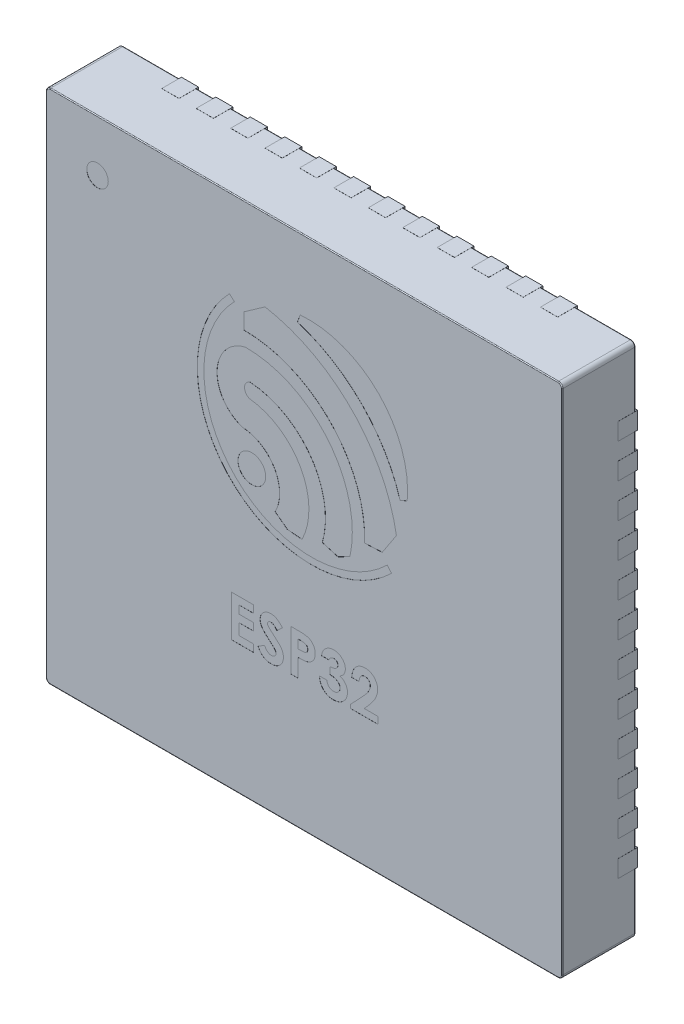
SolidWorks part; units mm, degrees
other "ESP32-SoC-6x6" parameters "D5"=0.3678, "D1"=3.1308, "D2"=3.0402, "D3"=0.4115, "D4"=0.3, "D6"=0.3296, "D7"=0.2637, "D8"=0.9806, "D10"=0.4, "D11"=0.25, "D9"=6
ref_plane "Front Plane" through (0, 0, 0) normal (0, 0, 1) x (1, 0, 0)
ref_plane "Top Plane" through (0, 0, 0) normal (0, 1, 0) x (1, 0, 0)
ref_plane "Right Plane" through (0, 0, 0) normal (1, 0, 0) x (0, 0, -1)
sketch "Sketch1" plane through (0, 0, 0) normal (0, 1, 0) x (1, 0, 0)
  line L1 (-3, -3) -> (3, -3)
  line L2 (-3, -3) -> (-3, 3)
  line L3 (-3, 3) -> (3, 3)
  line L4 (3, -3) -> (3, 3)
  line L5 (-3, -3) -> (3, 3) construction
  line L6 (-3, 3) -> (3, -3) construction
  point P0 (0, 0)
  dimension "D1" = 6
  dimension "D2" = 6
extrude "Boss-Extrude1" add sketch "Sketch1" along normal blind 0.85
fillet "Fillet1" radius 0.05 4 edges at (3, 0.425, -3) (3, 0.425, 3) (-3, 0.425, 3) (-3, 0.425, -3)
fillet "Fillet2" radius 0.01 16 edges at (2.9854, 0.85, 2.9854) (0, 0.85, 3) (-2.9854, 0.85, 2.9854) (-3, 0.85, 0) (-2.9854, 0.85, -2.9854) (0, 0.85, -3) (2.9854, 0.85, -2.9854) (3, 0.85, 0) (3, 0, 0) (2.9854, 0, -2.9854) (0, 0, -3) (2.9854, 0, 2.9854) (0, 0, 3) (-2.9854, 0, 2.9854) (-3, 0, 0) (-2.9854, 0, -2.9854)
sketch "Sketch2" plane through (0, 0, 0) normal (0, -1, 0) x (1, 0, 0)
  line L0 (1.85, 2.15) -> (2.15, 1.85)
  line L1 (-2.05, -2.15) -> (2.05, -2.15)
  line L2 (-2.15, -2.05) -> (-2.15, 2.05)
  line L3 (-2.05, 2.15) -> (1.85, 2.15)
  line L4 (2.15, -2.05) -> (2.15, 1.85)
  line L5 (-2.1207, -2.1207) -> (2.15, 2.15) construction
  line L6 (-2.1207, 2.1207) -> (2.1207, -2.1207) construction
  line L7 (1.85, 2.15) -> (2.15, 2.15) construction
  line L8 (2.15, 1.85) -> (2.15, 2.15) construction
  line L9 (-2.15, 2.15) -> (-2.05, 2.15) construction
  line L10 (-2.15, 2.15) -> (-2.1207, 2.1207) construction
  line L11 (-2.15, 2.05) -> (-2.15, 2.15) construction
  line L12 (-2.15, -2.15) -> (-2.15, -2.05) construction
  line L13 (-2.15, -2.15) -> (-2.1207, -2.1207) construction
  line L14 (-2.15, -2.15) -> (-2.05, -2.15) construction
  line L15 (2.15, -2.15) -> (2.15, -2.05) construction
  line L16 (2.1207, -2.1207) -> (2.15, -2.15) construction
  line L17 (2.05, -2.15) -> (2.15, -2.15) construction
  line L18 (0, -1000) -> (0, 49000) construction
  line L23 (-0.3, 3.001) -> (-0.1, 3.001)
  line L24 (-0.3, 3.001) -> (-0.3, 2.601)
  line L25 (-0.3, 2.601) -> (-0.1, 2.601)
  line L26 (-0.1, 3.001) -> (-0.1, 2.601)
  line L27 (-0.3, 3.001) -> (-0.1, 2.601) construction
  line L28 (-0.3, 2.601) -> (-0.1, 3.001) construction
  line L30 (-0.7, 3.001) -> (-0.7, 2.601)
  line L31 (-0.7, 3.001) -> (-0.5, 3.001)
  line L32 (-0.5, 3.001) -> (-0.5, 2.601)
  line L33 (-0.7, 2.601) -> (-0.5, 2.601)
  line L34 (-0.7, 2.601) -> (-0.5, 3.001) construction
  line L35 (-0.7, 3.001) -> (-0.5, 2.601) construction
  line L36 (-1.1, 3.001) -> (-1.1, 2.601)
  line L37 (-1.1, 3.001) -> (-0.9, 3.001)
  line L38 (-0.9, 3.001) -> (-0.9, 2.601)
  line L39 (-1.1, 2.601) -> (-0.9, 2.601)
  line L40 (-1.1, 2.601) -> (-0.9, 3.001) construction
  line L41 (-1.1, 3.001) -> (-0.9, 2.601) construction
  line L42 (-1.5, 3.001) -> (-1.5, 2.601)
  line L43 (-1.5, 3.001) -> (-1.3, 3.001)
  line L44 (-1.3, 3.001) -> (-1.3, 2.601)
  line L45 (-1.5, 2.601) -> (-1.3, 2.601)
  line L46 (-1.5, 2.601) -> (-1.3, 3.001) construction
  line L47 (-1.5, 3.001) -> (-1.3, 2.601) construction
  line L48 (-0.3, 3.001) -> (-0.7, 3.001) construction
  line L49 (-1.9, 3.001) -> (-1.9, 2.601)
  line L66 (-1.9, 3.001) -> (-1.7, 3.001)
  line L162 (-1000, 0) -> (49000, 0) construction
  line L163 (-3, 3) -> (3, 3) construction
  line L164 (-1.7, 3.001) -> (-1.7, 2.601)
  line L165 (-1.9, 2.601) -> (-1.7, 2.601)
  line L166 (-1.9, 2.601) -> (-1.7, 3.001) construction
  line L167 (-1.9, 3.001) -> (-1.7, 2.601) construction
  line L168 (-2.3, 3.001) -> (-2.3, 2.601)
  line L169 (-2.3, 3.001) -> (-2.1, 3.001)
  line L170 (-2.1, 3.001) -> (-2.1, 2.601)
  line L171 (-2.3, 2.601) -> (-2.1, 2.601)
  line L172 (-2.3, 2.601) -> (-2.1, 3.001) construction
  line L173 (-2.3, 3.001) -> (-2.1, 2.601) construction
  line L174 (2.3, 3.001) -> (2.1, 2.601) construction
  line L175 (2.3, 2.601) -> (2.1, 3.001) construction
  line L176 (1.9, 3.001) -> (1.7, 2.601) construction
  line L177 (1.9, 2.601) -> (1.7, 3.001) construction
  line L178 (0.3, 3.001) -> (0.7, 3.001) construction
  line L179 (1.5, 3.001) -> (1.3, 2.601) construction
  line L180 (1.5, 2.601) -> (1.3, 3.001) construction
  line L181 (1.1, 3.001) -> (0.9, 2.601) construction
  line L182 (1.1, 2.601) -> (0.9, 3.001) construction
  line L183 (0.7, 3.001) -> (0.5, 2.601) construction
  line L184 (0.7, 2.601) -> (0.5, 3.001) construction
  line L185 (0.3, 2.601) -> (0.1, 3.001) construction
  line L186 (0.3, 3.001) -> (0.1, 2.601) construction
  line L187 (2.3, 2.601) -> (2.1, 2.601)
  line L188 (2.1, 3.001) -> (2.1, 2.601)
  line L189 (2.3, 3.001) -> (2.1, 3.001)
  line L190 (2.3, 3.001) -> (2.3, 2.601)
  line L191 (1.9, 2.601) -> (1.7, 2.601)
  line L192 (1.7, 3.001) -> (1.7, 2.601)
  line L193 (1.9, 3.001) -> (1.7, 3.001)
  line L194 (1.9, 3.001) -> (1.9, 2.601)
  line L195 (1.5, 2.601) -> (1.3, 2.601)
  line L196 (1.3, 3.001) -> (1.3, 2.601)
  line L197 (1.5, 3.001) -> (1.3, 3.001)
  line L198 (1.5, 3.001) -> (1.5, 2.601)
  line L199 (1.1, 2.601) -> (0.9, 2.601)
  line L200 (0.9, 3.001) -> (0.9, 2.601)
  line L201 (1.1, 3.001) -> (0.9, 3.001)
  line L202 (1.1, 3.001) -> (1.1, 2.601)
  line L203 (0.7, 2.601) -> (0.5, 2.601)
  line L204 (0.5, 3.001) -> (0.5, 2.601)
  line L205 (0.7, 3.001) -> (0.5, 3.001)
  line L206 (0.7, 3.001) -> (0.7, 2.601)
  line L207 (0.1, 3.001) -> (0.1, 2.601)
  line L208 (0.3, 2.601) -> (0.1, 2.601)
  line L209 (0.3, 3.001) -> (0.3, 2.601)
  line L210 (0.3, 3.001) -> (0.1, 3.001)
  line L211 (0.3, -3.001) -> (0.1, -2.601) construction
  line L212 (0.3, -2.601) -> (0.1, -3.001) construction
  line L213 (0.7, -2.601) -> (0.5, -3.001) construction
  line L214 (0.7, -3.001) -> (0.5, -2.601) construction
  line L215 (1.1, -2.601) -> (0.9, -3.001) construction
  line L216 (1.1, -3.001) -> (0.9, -2.601) construction
  line L217 (1.5, -2.601) -> (1.3, -3.001) construction
  line L218 (1.5, -3.001) -> (1.3, -2.601) construction
  line L219 (0.3, -3.001) -> (0.7, -3.001) construction
  line L220 (1.9, -2.601) -> (1.7, -3.001) construction
  line L221 (1.9, -3.001) -> (1.7, -2.601) construction
  line L222 (2.3, -2.601) -> (2.1, -3.001) construction
  line L223 (2.3, -3.001) -> (2.1, -2.601) construction
  line L224 (-2.3, -3.001) -> (-2.1, -2.601) construction
  line L225 (-2.3, -2.601) -> (-2.1, -3.001) construction
  line L226 (-1.9, -3.001) -> (-1.7, -2.601) construction
  line L227 (-1.9, -2.601) -> (-1.7, -3.001) construction
  line L228 (-0.3, -3.001) -> (-0.7, -3.001) construction
  line L229 (-1.5, -3.001) -> (-1.3, -2.601) construction
  line L230 (-1.5, -2.601) -> (-1.3, -3.001) construction
  line L231 (-1.1, -3.001) -> (-0.9, -2.601) construction
  line L232 (-1.1, -2.601) -> (-0.9, -3.001) construction
  line L233 (-0.7, -3.001) -> (-0.5, -2.601) construction
  line L234 (-0.7, -2.601) -> (-0.5, -3.001) construction
  line L235 (-0.3, -2.601) -> (-0.1, -3.001) construction
  line L236 (-0.3, -3.001) -> (-0.1, -2.601) construction
  line L237 (0.3, -3.001) -> (0.1, -3.001)
  line L238 (0.3, -3.001) -> (0.3, -2.601)
  line L239 (0.3, -2.601) -> (0.1, -2.601)
  line L240 (0.1, -3.001) -> (0.1, -2.601)
  line L241 (0.7, -3.001) -> (0.7, -2.601)
  line L242 (0.7, -3.001) -> (0.5, -3.001)
  line L243 (0.5, -3.001) -> (0.5, -2.601)
  line L244 (0.7, -2.601) -> (0.5, -2.601)
  line L245 (1.1, -3.001) -> (1.1, -2.601)
  line L246 (1.1, -3.001) -> (0.9, -3.001)
  line L247 (0.9, -3.001) -> (0.9, -2.601)
  line L248 (1.1, -2.601) -> (0.9, -2.601)
  line L249 (1.5, -3.001) -> (1.5, -2.601)
  line L250 (1.5, -3.001) -> (1.3, -3.001)
  line L251 (1.3, -3.001) -> (1.3, -2.601)
  line L252 (1.5, -2.601) -> (1.3, -2.601)
  line L253 (1.9, -3.001) -> (1.9, -2.601)
  line L254 (1.9, -3.001) -> (1.7, -3.001)
  line L255 (1.7, -3.001) -> (1.7, -2.601)
  line L256 (1.9, -2.601) -> (1.7, -2.601)
  line L257 (2.3, -3.001) -> (2.3, -2.601)
  line L258 (2.3, -3.001) -> (2.1, -3.001)
  line L259 (2.1, -3.001) -> (2.1, -2.601)
  line L260 (2.3, -2.601) -> (2.1, -2.601)
  line L261 (-2.3, -2.601) -> (-2.1, -2.601)
  line L262 (-2.1, -3.001) -> (-2.1, -2.601)
  line L263 (-2.3, -3.001) -> (-2.1, -3.001)
  line L264 (-2.3, -3.001) -> (-2.3, -2.601)
  line L265 (-1.9, -2.601) -> (-1.7, -2.601)
  line L266 (-1.7, -3.001) -> (-1.7, -2.601)
  line L267 (-1.9, -3.001) -> (-1.7, -3.001)
  line L268 (-1.9, -3.001) -> (-1.9, -2.601)
  line L269 (-1.5, -2.601) -> (-1.3, -2.601)
  line L270 (-1.3, -3.001) -> (-1.3, -2.601)
  line L271 (-1.5, -3.001) -> (-1.3, -3.001)
  line L272 (-1.5, -3.001) -> (-1.5, -2.601)
  line L273 (-1.1, -2.601) -> (-0.9, -2.601)
  line L274 (-0.9, -3.001) -> (-0.9, -2.601)
  line L275 (-1.1, -3.001) -> (-0.9, -3.001)
  line L276 (-1.1, -3.001) -> (-1.1, -2.601)
  line L277 (-0.7, -2.601) -> (-0.5, -2.601)
  line L278 (-0.5, -3.001) -> (-0.5, -2.601)
  line L279 (-0.7, -3.001) -> (-0.5, -3.001)
  line L280 (-0.7, -3.001) -> (-0.7, -2.601)
  line L281 (-0.1, -3.001) -> (-0.1, -2.601)
  line L282 (-0.3, -2.601) -> (-0.1, -2.601)
  line L283 (-0.3, -3.001) -> (-0.3, -2.601)
  line L284 (-0.3, -3.001) -> (-0.1, -3.001)
  line L285 (3.001, 0.3) -> (2.601, 0.1) construction
  line L286 (2.601, 0.3) -> (3.001, 0.1) construction
  line L287 (2.601, 0.7) -> (3.001, 0.5) construction
  line L288 (3.001, 0.7) -> (2.601, 0.5) construction
  line L289 (2.601, 1.1) -> (3.001, 0.9) construction
  line L290 (3.001, 1.1) -> (2.601, 0.9) construction
  line L291 (2.601, 1.5) -> (3.001, 1.3) construction
  line L292 (3.001, 1.5) -> (2.601, 1.3) construction
  line L293 (3.001, 0.3) -> (3.001, 0.7) construction
  line L294 (2.601, 1.9) -> (3.001, 1.7) construction
  line L295 (3.001, 1.9) -> (2.601, 1.7) construction
  line L296 (2.601, 2.3) -> (3.001, 2.1) construction
  line L297 (3.001, 2.3) -> (2.601, 2.1) construction
  line L298 (3.001, -2.3) -> (2.601, -2.1) construction
  line L299 (2.601, -2.3) -> (3.001, -2.1) construction
  line L300 (3.001, -1.9) -> (2.601, -1.7) construction
  line L301 (2.601, -1.9) -> (3.001, -1.7) construction
  line L302 (3.001, -0.3) -> (3.001, -0.7) construction
  line L303 (3.001, -1.5) -> (2.601, -1.3) construction
  line L304 (2.601, -1.5) -> (3.001, -1.3) construction
  line L305 (3.001, -1.1) -> (2.601, -0.9) construction
  line L306 (2.601, -1.1) -> (3.001, -0.9) construction
  line L307 (3.001, -0.7) -> (2.601, -0.5) construction
  line L308 (2.601, -0.7) -> (3.001, -0.5) construction
  line L309 (2.601, -0.3) -> (3.001, -0.1) construction
  line L310 (3.001, -0.3) -> (2.601, -0.1) construction
  line L311 (3.001, 0.3) -> (3.001, 0.1)
  line L312 (3.001, 0.3) -> (2.601, 0.3)
  line L313 (2.601, 0.3) -> (2.601, 0.1)
  line L314 (3.001, 0.1) -> (2.601, 0.1)
  line L315 (3.001, 0.7) -> (2.601, 0.7)
  line L316 (3.001, 0.7) -> (3.001, 0.5)
  line L317 (3.001, 0.5) -> (2.601, 0.5)
  line L318 (2.601, 0.7) -> (2.601, 0.5)
  line L319 (3.001, 1.1) -> (2.601, 1.1)
  line L320 (3.001, 1.1) -> (3.001, 0.9)
  line L321 (3.001, 0.9) -> (2.601, 0.9)
  line L322 (2.601, 1.1) -> (2.601, 0.9)
  line L323 (3.001, 1.5) -> (2.601, 1.5)
  line L324 (3.001, 1.5) -> (3.001, 1.3)
  line L325 (3.001, 1.3) -> (2.601, 1.3)
  line L326 (2.601, 1.5) -> (2.601, 1.3)
  line L327 (3.001, 1.9) -> (2.601, 1.9)
  line L328 (3.001, 1.9) -> (3.001, 1.7)
  line L329 (3.001, 1.7) -> (2.601, 1.7)
  line L330 (2.601, 1.9) -> (2.601, 1.7)
  line L331 (3.001, 2.3) -> (2.601, 2.3)
  line L332 (3.001, 2.3) -> (3.001, 2.1)
  line L333 (3.001, 2.1) -> (2.601, 2.1)
  line L334 (2.601, 2.3) -> (2.601, 2.1)
  line L335 (2.601, -2.3) -> (2.601, -2.1)
  line L336 (3.001, -2.1) -> (2.601, -2.1)
  line L337 (3.001, -2.3) -> (3.001, -2.1)
  line L338 (3.001, -2.3) -> (2.601, -2.3)
  line L339 (2.601, -1.9) -> (2.601, -1.7)
  line L340 (3.001, -1.7) -> (2.601, -1.7)
  line L341 (3.001, -1.9) -> (3.001, -1.7)
  line L342 (3.001, -1.9) -> (2.601, -1.9)
  line L343 (2.601, -1.5) -> (2.601, -1.3)
  line L344 (3.001, -1.3) -> (2.601, -1.3)
  line L345 (3.001, -1.5) -> (3.001, -1.3)
  line L346 (3.001, -1.5) -> (2.601, -1.5)
  line L347 (2.601, -1.1) -> (2.601, -0.9)
  line L348 (3.001, -0.9) -> (2.601, -0.9)
  line L349 (3.001, -1.1) -> (3.001, -0.9)
  line L350 (3.001, -1.1) -> (2.601, -1.1)
  line L351 (2.601, -0.7) -> (2.601, -0.5)
  line L352 (3.001, -0.5) -> (2.601, -0.5)
  line L353 (3.001, -0.7) -> (3.001, -0.5)
  line L354 (3.001, -0.7) -> (2.601, -0.7)
  line L355 (3.001, -0.1) -> (2.601, -0.1)
  line L356 (2.601, -0.3) -> (2.601, -0.1)
  line L357 (3.001, -0.3) -> (2.601, -0.3)
  line L358 (3.001, -0.3) -> (3.001, -0.1)
  line L359 (-3.001, -0.3) -> (-2.601, -0.1) construction
  line L360 (-2.601, -0.3) -> (-3.001, -0.1) construction
  line L361 (-2.601, -0.7) -> (-3.001, -0.5) construction
  line L362 (-3.001, -0.7) -> (-2.601, -0.5) construction
  line L363 (-2.601, -1.1) -> (-3.001, -0.9) construction
  line L364 (-3.001, -1.1) -> (-2.601, -0.9) construction
  line L365 (-2.601, -1.5) -> (-3.001, -1.3) construction
  line L366 (-3.001, -1.5) -> (-2.601, -1.3) construction
  line L367 (-3.001, -0.3) -> (-3.001, -0.7) construction
  line L368 (-2.601, -1.9) -> (-3.001, -1.7) construction
  line L369 (-3.001, -1.9) -> (-2.601, -1.7) construction
  line L370 (-2.601, -2.3) -> (-3.001, -2.1) construction
  line L371 (-3.001, -2.3) -> (-2.601, -2.1) construction
  line L372 (-3.001, 2.3) -> (-2.601, 2.1) construction
  line L373 (-2.601, 2.3) -> (-3.001, 2.1) construction
  line L374 (-3.001, 1.9) -> (-2.601, 1.7) construction
  line L375 (-2.601, 1.9) -> (-3.001, 1.7) construction
  line L376 (-3.001, 0.3) -> (-3.001, 0.7) construction
  line L377 (-3.001, 1.5) -> (-2.601, 1.3) construction
  line L378 (-2.601, 1.5) -> (-3.001, 1.3) construction
  line L379 (-3.001, 1.1) -> (-2.601, 0.9) construction
  line L380 (-2.601, 1.1) -> (-3.001, 0.9) construction
  line L381 (-3.001, 0.7) -> (-2.601, 0.5) construction
  line L382 (-2.601, 0.7) -> (-3.001, 0.5) construction
  line L383 (-2.601, 0.3) -> (-3.001, 0.1) construction
  line L384 (-3.001, 0.3) -> (-2.601, 0.1) construction
  line L385 (-3.001, -0.3) -> (-3.001, -0.1)
  line L386 (-3.001, -0.3) -> (-2.601, -0.3)
  line L387 (-2.601, -0.3) -> (-2.601, -0.1)
  line L388 (-3.001, -0.1) -> (-2.601, -0.1)
  line L389 (-3.001, -0.7) -> (-2.601, -0.7)
  line L390 (-3.001, -0.7) -> (-3.001, -0.5)
  line L391 (-3.001, -0.5) -> (-2.601, -0.5)
  line L392 (-2.601, -0.7) -> (-2.601, -0.5)
  line L393 (-3.001, -1.1) -> (-2.601, -1.1)
  line L394 (-3.001, -1.1) -> (-3.001, -0.9)
  line L395 (-3.001, -0.9) -> (-2.601, -0.9)
  line L396 (-2.601, -1.1) -> (-2.601, -0.9)
  line L397 (-3.001, -1.5) -> (-2.601, -1.5)
  line L398 (-3.001, -1.5) -> (-3.001, -1.3)
  line L399 (-3.001, -1.3) -> (-2.601, -1.3)
  line L400 (-2.601, -1.5) -> (-2.601, -1.3)
  line L401 (-3.001, -1.9) -> (-2.601, -1.9)
  line L402 (-3.001, -1.9) -> (-3.001, -1.7)
  line L403 (-3.001, -1.7) -> (-2.601, -1.7)
  line L404 (-2.601, -1.9) -> (-2.601, -1.7)
  line L405 (-3.001, -2.3) -> (-2.601, -2.3)
  line L406 (-3.001, -2.3) -> (-3.001, -2.1)
  line L407 (-3.001, -2.1) -> (-2.601, -2.1)
  line L408 (-2.601, -2.3) -> (-2.601, -2.1)
  line L409 (-2.601, 2.3) -> (-2.601, 2.1)
  line L410 (-3.001, 2.1) -> (-2.601, 2.1)
  line L411 (-3.001, 2.3) -> (-3.001, 2.1)
  line L412 (-3.001, 2.3) -> (-2.601, 2.3)
  line L413 (-2.601, 1.9) -> (-2.601, 1.7)
  line L414 (-3.001, 1.7) -> (-2.601, 1.7)
  line L415 (-3.001, 1.9) -> (-3.001, 1.7)
  line L416 (-3.001, 1.9) -> (-2.601, 1.9)
  line L417 (-2.601, 1.5) -> (-2.601, 1.3)
  line L418 (-3.001, 1.3) -> (-2.601, 1.3)
  line L419 (-3.001, 1.5) -> (-3.001, 1.3)
  line L420 (-3.001, 1.5) -> (-2.601, 1.5)
  line L421 (-2.601, 1.1) -> (-2.601, 0.9)
  line L422 (-3.001, 0.9) -> (-2.601, 0.9)
  line L423 (-3.001, 1.1) -> (-3.001, 0.9)
  line L424 (-3.001, 1.1) -> (-2.601, 1.1)
  line L425 (-2.601, 0.7) -> (-2.601, 0.5)
  line L426 (-3.001, 0.5) -> (-2.601, 0.5)
  line L427 (-3.001, 0.7) -> (-3.001, 0.5)
  line L428 (-3.001, 0.7) -> (-2.601, 0.7)
  line L429 (-3.001, 0.1) -> (-2.601, 0.1)
  line L430 (-2.601, 0.3) -> (-2.601, 0.1)
  line L431 (-3.001, 0.3) -> (-2.601, 0.3)
  line L432 (-3.001, 0.3) -> (-3.001, 0.1)
  arc A0 (-2.05, 2.15) -> (-2.15, 2.05) centre (-2.05, 2.05) ccw
  arc A1 (-2.15, -2.05) -> (-2.05, -2.15) centre (-2.05, -2.05) ccw
  arc A2 (2.05, -2.15) -> (2.15, -2.05) centre (2.05, -2.05) ccw
  point P0 (0, 0)
  point P12 (-0.2, 2.801)
  point P76 (0.2, 2.801)
  point P125 (0.2, -2.801)
  point P126 (-0.2, -2.801)
  point P175 (2.801, 0.2)
  point P176 (2.801, -0.2)
  point P225 (-2.801, -0.2)
  point P226 (-2.801, 0.2)
  dimension "D5" = 0.2
  dimension "D1" = 4.3
  dimension "D2" = 4.3
  dimension "D4" = 45
  dimension "D6" = 0.4
  dimension "D7" = 0.2
  dimension "D8" = 0.2
  dimension "D11" = 0.001
  dimension "D3" = 0.3
extrude "Boss-Extrude2" add sketch "Sketch2" along normal blind 0.025 and the other way blind 0.203
sketch "Sketch3" plane through (0, 0.85, 0) normal (0, 1, 0) x (1, 0, 0)
  line L7 (-3, 1.495) -> (3, 1.495) construction
  line L8 (-3, 3) -> (-3, -3) construction
  line L9 (2.95, -3) -> (-2.95, -3) construction
  line L11 (3, 2.95) -> (3, -2.95) construction
  line L12 (-1.1156, -0.8875) -> (-1.1984, -0.9227)
  line L13 (0.0455, -2.1731) -> (0.0771, -2.0851)
  line L14 (-0.7041, -0.2516) -> (-0.9082, -0.2603)
  line L15 (-0.9082, -0.2603) -> (-1.0732, -0.5122)
  line L16 (0.453, -2.05) -> (0.7007, -1.8763)
  line L17 (0.7007, -1.8763) -> (0.7007, -1.6937)
  line L18 (0.8092, -1.9249) -> (0.8669, -1.9759)
  line L19 (-1.017, -0.1038) -> (-0.9657, -0.1612)
  line L20 (0.3358, -0.0475) -> (0.1938, 0.06)
  line L21 (0.1938, 0.06) -> (0.0232, 0.075)
  line L22 (-0.2122, -0.0121) -> (-0.3925, 0.0416)
  line L23 (-0.3925, 0.0416) -> (-0.533, -0.0287)
  line L24 (0, 0) -> (0, 2.99) construction
  line L25 (2.95, 2.99) -> (-2.95, 2.99) construction
  circle A10 centre (2.4, -2.4) radius 0.125
  arc A11 (-1.1156, -0.8875) -> (0.0771, -2.0851) centre (0.6069, -0.3648) ccw
  arc A12 (-1.0732, -0.5122) -> (0.453, -2.05) centre (0.7891, -0.1902) ccw
  arc A13 (0.68, -1.5308) -> (0.7154, -0.7064) centre (0.5834, -1.1137) ccw
  arc A14 (0.8669, -1.9759) -> (-1.017, -0.1038) centre (-0.0872, -1.0521) ccw
  circle A15 centre (0.6069, -0.3449) radius 0.1612
  arc A16 (-0.2122, -0.0121) -> (0.6283, -1.2049) centre (0.6878, -0.2705) ccw
  arc A17 (0.3358, -0.0475) -> (0.7154, -0.7064) centre (0.7346, -0.2566) ccw
  arc A18 (0.0232, 0.075) -> (0.6315, -1.0357) centre (0.7174, -0.2667) ccw
  arc A19 (-0.533, -0.0287) -> (0.68, -1.5308) centre (0.6805, -0.2896) ccw
  arc A20 (0.8092, -1.9249) -> (-0.9657, -0.1612) centre (-0.0872, -1.0521) ccw
  arc A21 (-0.7041, -0.2516) -> (0.7007, -1.6937) centre (0.6993, -0.2898) ccw
  arc A22 (0.6315, -1.0357) -> (0.6283, -1.2049) centre (0.6031, -1.1198) cw
  arc A23 (-1.1984, -0.9227) -> (0.0455, -2.1731) centre (-0.0499, -1.0241) ccw
  text T0 "ESP32" font "Century Gothic" height 0.48
  point P0 (0, 1.495)
  point P52 (0, 0)
  dimension "D2" = 0.25
  dimension "D3" = 0.6
  dimension "D4" = 0.6
extrude "Cut-Extrude1" cut sketch "Sketch3" against normal blind 0.001
move or copy body "Body-Move/Copy1" bodies to move or copy 131 copy no rotation origin (0, 0, 0) rotation axis (0, 0.7071, 0.7071) rotation angle 180
move or copy body "Body-Move/Copy2" bodies to move or copy 132 copy no translate (0, 0, 0.025)
equation "\"D8@Sketch2\"=\"D10@Sketch2\"/2"
equation "\"D1@Sketch1\"=\"D2@Sketch1\""
equation "\"D1@Sketch2\"=\"D2@Sketch2\""
equation "\"D4@Sketch3\"=\"D3@Sketch3\""
